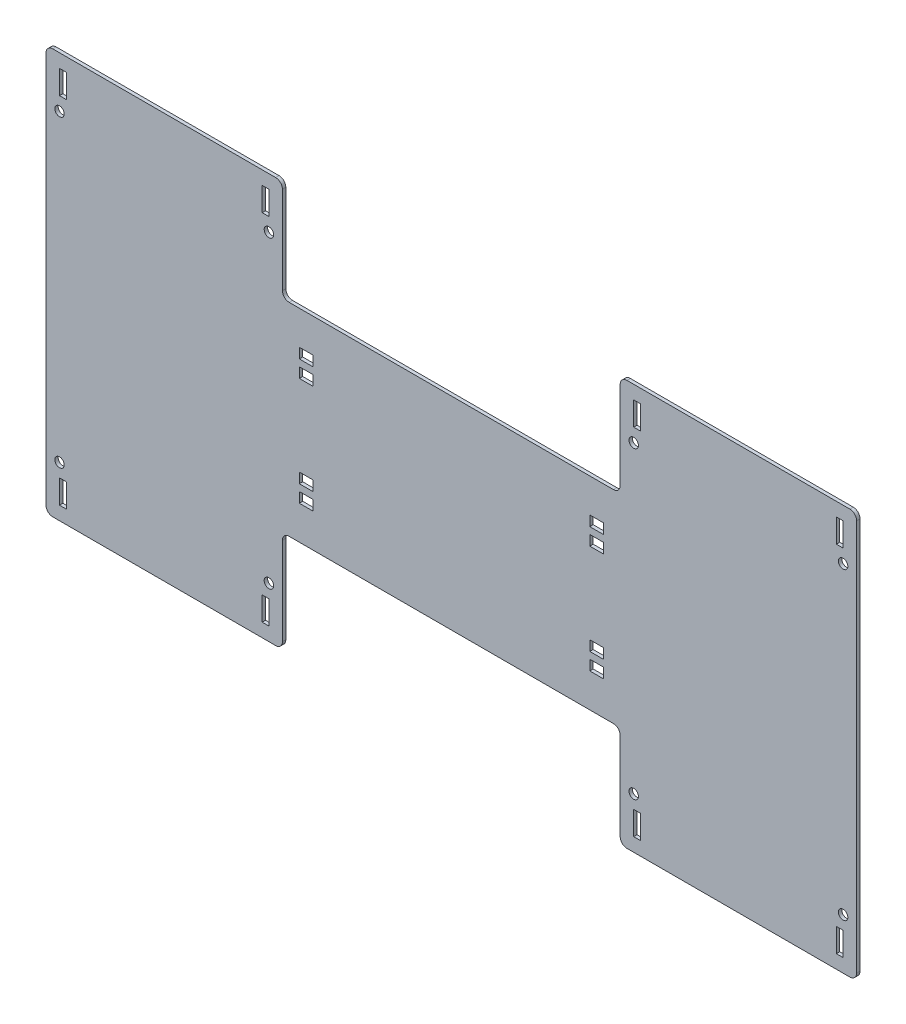
SolidWorks part; units mm, degrees
ref_plane "前视基准面" through (0, 0, 0) normal (0, 0, 1) x (1, 0, 0)
ref_plane "上视基准面" through (0, 0, 0) normal (0, 1, 0) x (1, 0, 0)
ref_plane "右视基准面" through (0, 0, 0) normal (1, 0, 0) x (0, 0, -1)
sketch "草图1" plane through (0, 0, 0) normal (0, 0, 1) x (1, 0, 0)
  line L0 (-250, 290) -> (-250, 160)
  line L1 (-240, 150) -> (240, 150)
  line L3 (-240, -150) -> (240, -150)
  line L5 (-250, 150) -> (250, -150) construction
  line L6 (-250, -150) -> (250, 150) construction
  line L7 (-260, -300) -> (-590, -300)
  line L8 (-600, -290) -> (-600, 290)
  line L9 (-590, 300) -> (-260, 300)
  line L10 (250, 160) -> (250, 290)
  line L11 (260, 300) -> (590, 300)
  line L12 (600, 290) -> (600, -290)
  line L13 (590, -300) -> (260, -300)
  line L14 (250, -290) -> (250, -160)
  line L15 (0, 0) -> (-50000, 0) construction
  line L16 (0, 0) -> (0, 50000) construction
  line L17 (-600, 300) -> (-250, -300) construction
  line L18 (-250, 300) -> (-600, -300) construction
  line L19 (-425, 0) -> (-425, 50000) construction
  line L20 (600, -300) -> (250, 300) construction
  line L21 (600, 300) -> (250, -300) construction
  line L22 (425, -5.3991) -> (425, 49994.6009) construction
  line L23 (-250, -160) -> (-250, -290)
  line L24 (-225, -60) -> (-205, -60)
  line L29 (-225, 100) -> (-205, 100)
  line L30 (-225, 100) -> (-225, 85)
  line L31 (-225, 85) -> (-205, 85)
  line L32 (-205, 100) -> (-205, 85)
  line L33 (-225, 100) -> (-205, 85) construction
  line L34 (-225, 85) -> (-205, 100) construction
  line L35 (-225, 75) -> (-205, 75)
  line L36 (-225, 75) -> (-225, 60)
  line L37 (-225, 60) -> (-205, 60)
  line L38 (-205, 75) -> (-205, 60)
  line L39 (-225, 75) -> (-205, 60) construction
  line L40 (-225, 60) -> (-205, 75) construction
  line L41 (-205, -75) -> (-205, -60)
  line L42 (-225, -75) -> (-205, -75)
  line L43 (-225, -75) -> (-225, -60)
  line L44 (-225, -85) -> (-205, -85)
  line L45 (-205, -100) -> (-205, -85)
  line L46 (-225, -100) -> (-205, -100)
  line L47 (-225, -100) -> (-225, -85)
  line L48 (225, -100) -> (225, -85)
  line L49 (225, -100) -> (205, -100)
  line L50 (205, -100) -> (205, -85)
  line L51 (225, -85) -> (205, -85)
  line L52 (225, 60) -> (205, 60)
  line L53 (205, 75) -> (205, 60)
  line L54 (225, 75) -> (205, 75)
  line L55 (225, 75) -> (225, 60)
  line L56 (225, 85) -> (205, 85)
  line L57 (205, 100) -> (205, 85)
  line L58 (225, 100) -> (205, 100)
  line L59 (225, 100) -> (225, 85)
  line L60 (225, -75) -> (225, -60)
  line L61 (225, -75) -> (205, -75)
  line L62 (205, -75) -> (205, -60)
  line L63 (225, -60) -> (205, -60)
  circle A0 centre (-580, -225) radius 7
  circle A2 centre (-580, 225) radius 7
  circle A3 centre (-270, 225) radius 7
  circle A4 centre (-270, -225) radius 7
  circle A5 centre (270, -225) radius 7
  circle A6 centre (580, -225) radius 7
  circle A7 centre (270, 225) radius 7
  circle A8 centre (580, 225) radius 7
  arc A9 (-600, -290) -> (-590, -300) centre (-590, -290) ccw
  arc A10 (-250, -290) -> (-260, -300) centre (-260, -290) cw
  arc A11 (-240, -150) -> (-250, -160) centre (-240, -160) ccw
  arc A12 (250, -160) -> (240, -150) centre (240, -160) ccw
  arc A13 (260, -300) -> (250, -290) centre (260, -290) cw
  arc A14 (590, -300) -> (600, -290) centre (590, -290) ccw
  arc A15 (600, 290) -> (590, 300) centre (590, 290) ccw
  arc A16 (250, 290) -> (260, 300) centre (260, 290) cw
  arc A17 (250, 160) -> (240, 150) centre (240, 160) cw
  arc A18 (-250, 160) -> (-240, 150) centre (-240, 160) ccw
  arc A19 (-250, 290) -> (-260, 300) centre (-260, 290) ccw
  arc A20 (-600, 290) -> (-590, 300) centre (-590, 290) cw
  point P0 (0, 0)
  point P21 (700, 0)
  point P23 (-425, 0)
  point P24 (-425, 0)
  point P25 (-425, 0)
  point P26 (-425, 0)
  point P27 (-425, 0)
  point P29 (227.862, 0)
  point P31 (700, 0)
  point P35 (425, 0)
  point P47 (425, 0)
  point P48 (701.5874, -711.8919)
  point P49 (704.4123, -4.7892)
  point P50 (-215, 92.5)
  point P55 (-215, 67.5)
  dimension "D7" = 20
  dimension "D9" = 14
  dimension "D18" = 10
  dimension "D1" = 600
  dimension "D2" = 350
  dimension "D3" = 500
  dimension "D4" = 350
  dimension "D5" = 600
  dimension "D6" = 300
  dimension "D8" = 75
  dimension "D10" = 300
  dimension "D11" = 15
  dimension "D12" = 20
  dimension "D13" = 15
  dimension "D14" = 20
  dimension "D15" = 10
  dimension "D16" = 50
  dimension "D17" = 25
extrude "凸台-拉伸1" add sketch "草图1" along normal mid plane 5
sketch "草图2" plane through (0, 0, 2.5) normal (0, 0, 1) x (1, 0, 0)
  line L0 (-260, 300) -> (-590, 300) construction
  line L1 (-580, 280) -> (-570, 280)
  line L2 (-580, 280) -> (-580, 245)
  line L3 (-580, 245) -> (-570, 245)
  line L4 (-570, 280) -> (-570, 245)
  line L5 (-580, 280) -> (-570, 245) construction
  line L6 (-580, 245) -> (-570, 280) construction
  line L7 (-600, 290) -> (-600, -290) construction
  line L8 (0, 0) -> (-50000, 0) construction
  line L9 (0, 0) -> (0, 50000) construction
  line L10 (-580, -245) -> (-570, -245)
  line L11 (-570, -280) -> (-570, -245)
  line L12 (-580, -280) -> (-570, -280)
  line L13 (-580, -280) -> (-580, -245)
  line L14 (580, -245) -> (570, -245)
  line L15 (580, -280) -> (570, -280)
  line L16 (580, -280) -> (580, -245)
  line L17 (570, -280) -> (570, -245)
  line L18 (580, 280) -> (570, 280)
  line L19 (580, 280) -> (580, 245)
  line L20 (570, 280) -> (570, 245)
  line L21 (580, 245) -> (570, 245)
  line L22 (-425, 0) -> (-425, 50000) construction
  line L23 (425, 0) -> (425, 50000) construction
  line L24 (270, -280) -> (270, -245)
  line L25 (270, -280) -> (280, -280)
  line L26 (280, -280) -> (280, -245)
  line L27 (270, -245) -> (280, -245)
  line L28 (270, 280) -> (270, 245)
  line L29 (270, 245) -> (280, 245)
  line L30 (280, 280) -> (280, 245)
  line L31 (270, 280) -> (280, 280)
  line L32 (-270, 245) -> (-280, 245)
  line L33 (-280, 280) -> (-280, 245)
  line L34 (-270, 280) -> (-280, 280)
  line L35 (-270, 280) -> (-270, 245)
  line L36 (-270, -280) -> (-270, -245)
  line L37 (-270, -280) -> (-280, -280)
  line L38 (-280, -280) -> (-280, -245)
  line L39 (-270, -245) -> (-280, -245)
  point P0 (-575, 262.5)
  dimension "D1" = 35
  dimension "D2" = 10
  dimension "D3" = 20
  dimension "D4" = 20
  dimension "D5" = 425
  dimension "D6" = 425
extrude "切除-拉伸3" cut sketch "草图2" against normal through all contours L33 L32 L35 L34 | L2 L3 L4 L1 | L13 L10 L11 L12 | L38 L39 L36 L37 | L17 L14 L16 L15 | L26 L27 L24 L25 | L28 L29 L30 L31 | L19 L21 L20 L18
